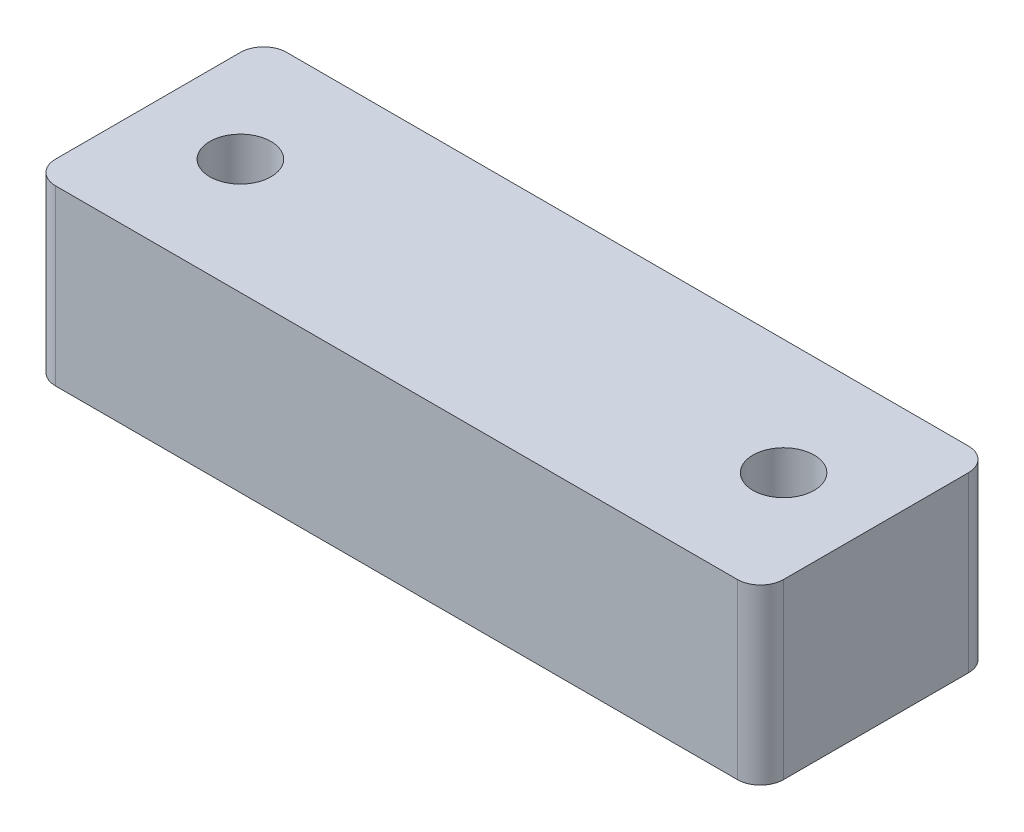
SolidWorks part; units mm, degrees
ref_plane "Front Plane" through (0, 0, 0) normal (0, 0, 1) x (1, 0, 0)
ref_plane "Top Plane" through (0, 0, 0) normal (0, 1, 0) x (1, 0, 0)
ref_plane "Right Plane" through (0, 0, 0) normal (1, 0, 0) x (0, 0, -1)
sketch "Sketch1" plane through (0, 0, 0) normal (0, 1, 0) x (1, 0, 0)
  line L1 (-11.5927, 11.4805) -> (47.4073, 11.4805)
  line L2 (-13.5927, 13.4805) -> (-13.5927, 29.4805)
  line L3 (-11.5927, 31.4805) -> (47.4073, 31.4805)
  line L4 (49.4073, 13.4805) -> (49.4073, 29.4805)
  arc A0 (-11.5927, 11.4805) -> (-13.5927, 13.4805) centre (-11.5927, 13.4805) cw
  arc A1 (47.4073, 11.4805) -> (49.4073, 13.4805) centre (47.4073, 13.4805) ccw
  arc A2 (47.4073, 31.4805) -> (49.4073, 29.4805) centre (47.4073, 29.4805) cw
  arc A3 (-13.5927, 29.4805) -> (-11.5927, 31.4805) centre (-11.5927, 29.4805) cw
  point P6 (-13.5927, 11.4805)
  point P11 (49.4073, 31.4805)
  point P14 (-13.5927, 31.4805)
  dimension "D3" = 2
  dimension "D1" = 20
  dimension "D2" = 63
extrude "Boss-Extrude1" add sketch "Sketch1" along normal blind 15
hole_wizard "M5 Clearance Hole1" positions "Sketch2" profile "Sketch3" hole size "M5" standard "ANSI Metric" end condition through all
sketch "Sketch2" plane through (0, 15, 0) normal (0, 1, 0) x (1, 0, 0)
  line L0 (-13.5927, 29.4805) -> (-13.5927, 13.4805) construction
  point P0 (-5.5927, 21.4805)
  point P2 (41.4073, 21.4805)
  dimension "D1" = 47
  dimension "D2" = 8
sketch "Sketch3" plane through (-5.5927, 15, -21.4805) normal (1, 0, 0) x (0, 0, 1)
  line L0 (0, 0) -> (0, 15)
  line L1 (0, 15) -> (2.65, 15)
  line L2 (2.65, 15) -> (2.65, 0)
  line L5 (2.65, 0) -> (0, 0)
  line L11 (0, -6.35) -> (0, 107.95) construction
  dimension "Thru Hole Dia." = 5.3
  dimension "Thru Hole Depth" = 15
